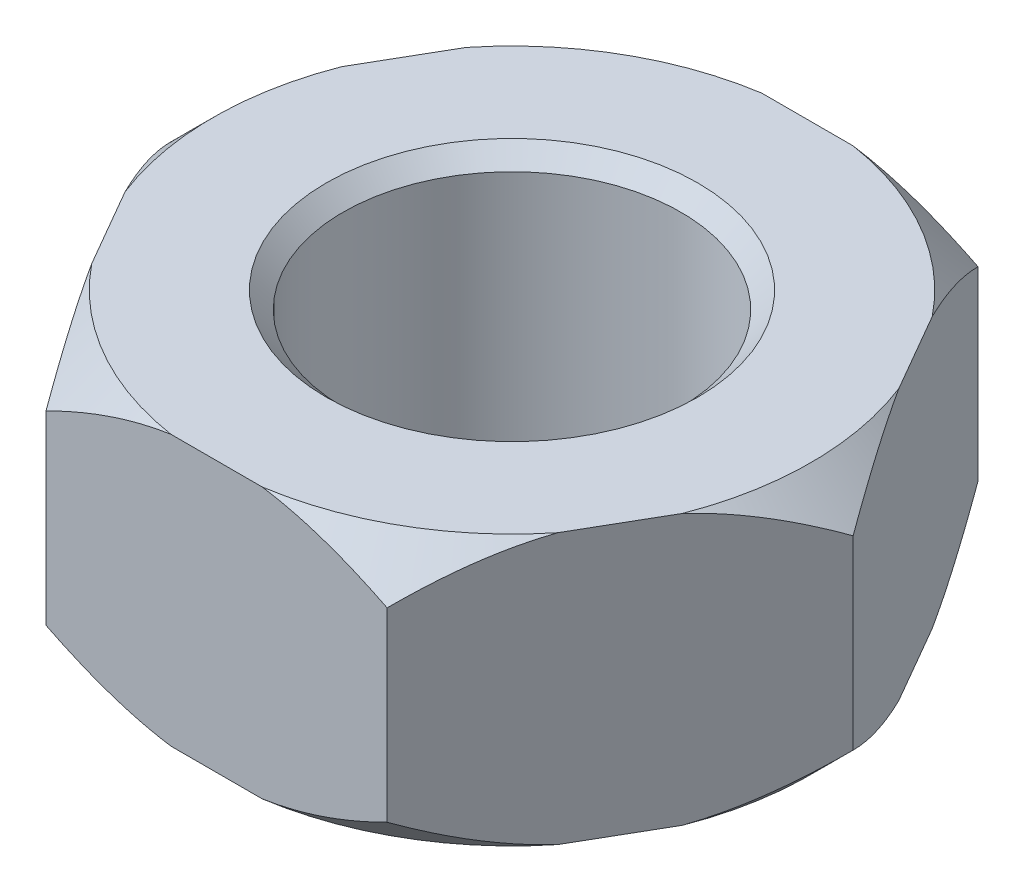
SolidWorks part; units mm, degrees
ref_plane "Спереди" through (0, 0, 0) normal (0, 0, 1) x (1, 0, 0)
ref_plane "Сверху" through (0, 0, 0) normal (0, 1, 0) x (1, 0, 0)
ref_plane "Справа" through (0, 0, 0) normal (1, 0, 0) x (0, 0, -1)
sketch "Эскиз1" plane through (0, 0, 0) normal (0, 1, 0) x (1, 0, 0)
  line L0 (-2.0207, 3.5) -> (2.0207, 3.5)
  line L1 (2.0207, 3.5) -> (4.0415, 0)
  line L2 (4.0415, 0) -> (2.0207, -3.5)
  line L3 (2.0207, -3.5) -> (-2.0207, -3.5)
  line L4 (-2.0207, -3.5) -> (-4.0415, 0)
  line L5 (-4.0415, 0) -> (-2.0207, 3.5)
  dimension "D5" = 3.5
  dimension "D2" = 120
  dimension "D3" = 120
  dimension "D4" = 120
  dimension "D6" = 3.5
  dimension "D7" = 3.5
  dimension "D8" = 3.5
  dimension "D9" = 3.5
  dimension "D10" = 120
  dimension "D11" = 3.5
extrude "Вытянуть1" add sketch "Эскиз1" against normal blind 3.2
sketch "Эскиз5" plane through (0, -3.2, 0) normal (0, -1, 0) x (1, 0, 0)
  circle A0 centre (0, 0) radius 2
  dimension "D1" = 4
extrude "Вырез-Вытянуть1" cut sketch "Эскиз5" against normal through all
ref_axis "Ось1" through (0, 0, 0) along (0, -1, 0)
ref_plane "Плоскость1" through (0, 0, 0) normal (0, 0, 1) x (1, 0, 0)
sketch "Эскиз4" plane through (0, 0, 0) normal (0, 0, 1) x (1, 0, 0)
  line L0 (-4.0415, -0.5) -> (-3.5415, 0)
  line L1 (-4.0415, -3.2) -> (-4.0415, 0) construction
  line L2 (-4.0415, 0) -> (-2.0207, 0) construction
  line L3 (-3.5415, 0) -> (-4.0415, 0)
  line L4 (-4.0415, 0) -> (-4.0415, -0.5)
  line L5 (-4.0415, -2.7) -> (-3.5415, -3.2)
  line L6 (-4.0415, -3.2) -> (-2.0207, -3.2) construction
  line L7 (-3.5415, -3.2) -> (-4.0415, -3.2)
  line L8 (-4.0415, -3.2) -> (-4.0415, -2.7)
  dimension "D1" = 0.5
  dimension "D2" = 0.5
  dimension "D3" = 0.5
  dimension "D4" = 0.5
revolve "Вырез-Повернуть1" cut sketch "Эскиз4" angle 360 about axis through (0, 0, 0) along (0, -1, 0)
chamfer "Фаска1" distance 0.2 angle 45 2 edges at (0, -3.2, -2) (0, 0, -2)
